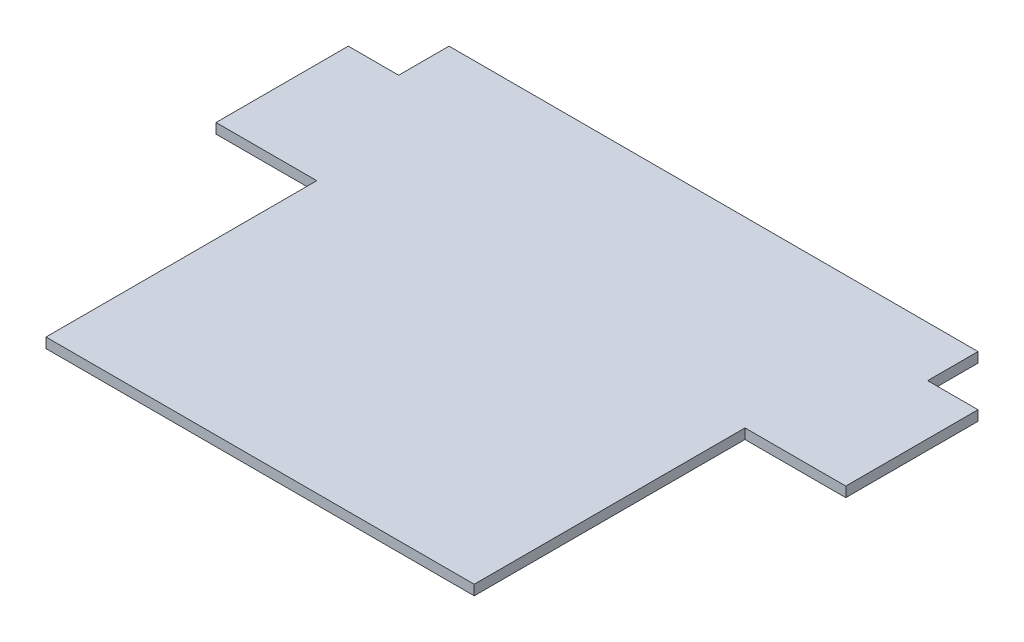
SolidWorks part; units mm, degrees
ref_plane "Front Plane" through (0, 0, 0) normal (0, 0, 1) x (1, 0, 0)
ref_plane "Top Plane" through (0, 0, 0) normal (0, 1, 0) x (1, 0, 0)
ref_plane "Right Plane" through (0, 0, 0) normal (1, 0, 0) x (0, 0, -1)
sketch "Sketch1" plane through (0, 0, 0) normal (0, 1, 0) x (1, 0, 0)
  line L0 (0, 0) -> (0, 72) construction
  line L2 (-34, 43) -> (-34, 0)
  line L5 (-34, 0) -> (34, 0)
  line L6 (-34, 43) -> (-50, 43)
  line L7 (-50, 43) -> (-50, 64)
  line L8 (-50, 64) -> (-42, 64)
  line L9 (-42, 64) -> (-42, 72)
  line L10 (-42, 72) -> (42, 72)
  line L11 (42, 64) -> (42, 72)
  line L12 (50, 64) -> (42, 64)
  line L13 (50, 43) -> (50, 64)
  line L14 (34, 43) -> (50, 43)
  line L15 (34, 43) -> (34, 0)
  point P4 (0, 63.3031)
  point P6 (0, 6.8444)
  point P13 (0, 62.9376)
  dimension "D1" = 21
  dimension "D2" = 43
  dimension "D3" = 8
  dimension "D4" = 68
  dimension "D5" = 100
  dimension "D6" = 84
extrude "Boss-Extrude1" add sketch "Sketch1" along normal blind 1.6
